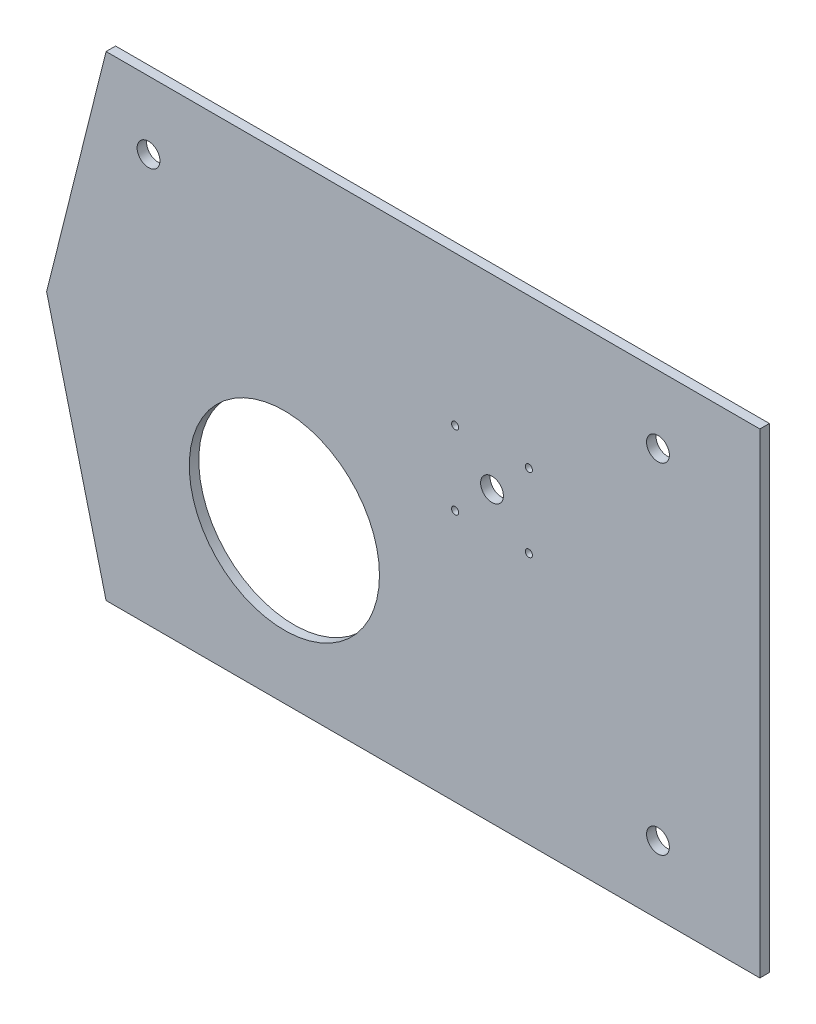
SolidWorks part; units mm, degrees
ref_plane "Front Plane" through (0, 0, 0) normal (0, 0, 1) x (1, 0, 0)
ref_plane "Top Plane" through (0, 0, 0) normal (0, 1, 0) x (1, 0, 0)
ref_plane "Right Plane" through (0, 0, 0) normal (1, 0, 0) x (0, 0, -1)
sketch "Sketch1" plane through (0, 0, 0) normal (0, 0, 1) x (1, 0, 0)
  line L0 (-50, 100) -> (-50, -100) construction
  line L1 (150, -100) -> (-150, -100)
  line L2 (150, -100) -> (150, 100)
  line L3 (150, 100) -> (-150, 100)
  line L4 (-150, -100) -> (-150, 100)
  line L5 (150, -100) -> (-150, 100) construction
  line L6 (150, 100) -> (-150, -100) construction
  line L7 (107.1429, 71.4286) -> (107.1429, -76.2286) construction
  line L8 (-150, 0) -> (150, 0) construction
  line L9 (-107.1429, 71.4286) -> (107.1429, 71.4286) construction
  line L10 (58.4824, 0.502) -> (16.1824, 0.502) construction
  line L11 (58.4824, 0.502) -> (58.4824, 42.802) construction
  line L12 (58.4824, 42.802) -> (16.1824, 42.802) construction
  line L13 (16.1824, 0.502) -> (16.1824, 42.802) construction
  line L14 (58.4824, 0.502) -> (16.1824, 42.802) construction
  line L15 (58.4824, 42.802) -> (16.1824, 0.502) construction
  line L16 (52.8324, 6.152) -> (21.8324, 6.152) construction
  line L17 (52.8324, 6.152) -> (52.8324, 37.152) construction
  line L18 (52.8324, 37.152) -> (21.8324, 37.152) construction
  line L19 (21.8324, 6.152) -> (21.8324, 37.152) construction
  line L20 (52.8324, 6.152) -> (21.8324, 37.152) construction
  line L21 (52.8324, 37.152) -> (21.8324, 6.152) construction
  line L22 (0, 71.4286) -> (107.1429, -71.4286) construction
  line L23 (-107.1429, 71.4286) -> (107.1429, -2.4) construction
  line L24 (-125, 100) -> (-125, -100) construction
  line L25 (-125, -100) -> (-150, 0)
  line L26 (-150, 0) -> (-125, 100)
  circle A0 centre (21.8324, 37.152) radius 1.5
  circle A1 centre (52.8324, 37.152) radius 1.5
  circle A2 centre (52.8324, 6.152) radius 1.5
  circle A3 centre (21.8324, 6.152) radius 1.5
  circle A4 centre (107.1429, 71.4286) radius 4.8
  circle A5 centre (107.1429, -71.4286) radius 4.8
  circle A6 centre (37.3324, 21.652) radius 4.8
  circle A7 centre (-50, -33.3333) radius 40
  circle A8 centre (-107.1429, 71.4286) radius 4.8
  point P0 (0, 0)
  point P6 (-107.1429, 71.4286)
  point P7 (107.1429, 71.4286)
  point P12 (37.3324, 21.652)
  point P27 (107.1429, 71.4286)
  point P28 (107.1429, -71.4286)
  point P36 (-50, -33.3333)
  point P43 (37.3324, 21.652)
  dimension "D5" = 3
  dimension "D6" = 3
  dimension "D7" = 3
  dimension "D8" = 3
  dimension "D13" = 9.6
  dimension "D14" = 9.6
  dimension "D15" = 9.6
  dimension "D16" = 80
  dimension "D17" = 9.6
  dimension "D1" = 300
  dimension "D2" = 200
  dimension "D3" = 42.3
  dimension "D4" = 42.3
  dimension "D9" = 31
  dimension "D10" = 31
  dimension "D11" = 42.8571
  dimension "D12" = 100
  dimension "D18" = 25
sketch "Sketch2" plane through (0, 0, 0) normal (0, 0, 1) x (1, 0, 0)
  line L1 (-108.014, -138.1365) -> (191.986, -138.1365)
  line L2 (-108.014, -138.1365) -> (-108.014, -142.1365)
  line L3 (-108.014, -142.1365) -> (191.986, -142.1365)
  line L4 (191.986, -138.1365) -> (191.986, -142.1365)
  line L5 (41.986, -142.1365) -> (41.986, -138.1365) construction
  line L6 (-108.014, -140.1365) -> (191.986, -140.1365) construction
  point P152 (41.986, -140.1365)
  dimension "D1" = 300
  dimension "D2" = 4
extrude "Boss-Extrude3" add sketch "Sketch1" along normal blind 4 contours L26 L25 L1 L2 L3 A8 A7 A6 A5 A4 A3 A2 A1 A0
equation "\"H\"= 200"
equation "\"L\" = 300"
equation "\"nema_internal\"= 31"
equation "\"nema_external\"= 42.3"
equation "\"bars\"= 9.60"
equation "\"trehead_rods\"= 8"
equation "\"hole_nema\"= 3"
equation "\"D1@Sketch1\"=\"L\""
equation "\"D2@Sketch1\"=\"H\""
equation "\"D3@Sketch1\"=\"nema_external\""
equation "\"D4@Sketch1\"=\"nema_external\""
equation "\"D5@Sketch1\"=\"hole_nema\""
equation "\"D6@Sketch1\"=\"hole_nema\""
equation "\"D7@Sketch1\"=\"hole_nema\""
equation "\"D8@Sketch1\"=\"hole_nema\""
equation "\"D9@Sketch1\"=\"nema_internal\""
equation "\"D10@Sketch1\"=\"nema_internal\""
equation "\"D11@Sketch1\"=\"L\"/7"
equation "\"D12@Sketch1\"=\"L\"/3"
equation "\"D13@Sketch1\"=\"bars\""
equation "\"D14@Sketch1\"=\"bars\""
equation "\"D15@Sketch1\"=\"bars\""
equation "\"ring_dimension_max\" = 80"
equation "\"thik_material\"= 4"
equation "\"D16@Sketch1\"= \"ring_dimension_max\""
equation "\"D17@Sketch1\"=\"bars\""
equation "\"D18@Sketch1\"=\"L\"/12"
equation "\"D1@Sketch2\"=\"L\""
equation "\"D2@Sketch2\"=\"thik_material\""
equation "\"kerf\"= 1"
equation "\"D1@Boss-Extrude3\"=\"thik_material\""
equation "\"ring_b\"=100"
equation "\"D19@Sketch1\"=\"ring_b\"-3"
equation "\"D20@Sketch1\"=\"ring_b\""
